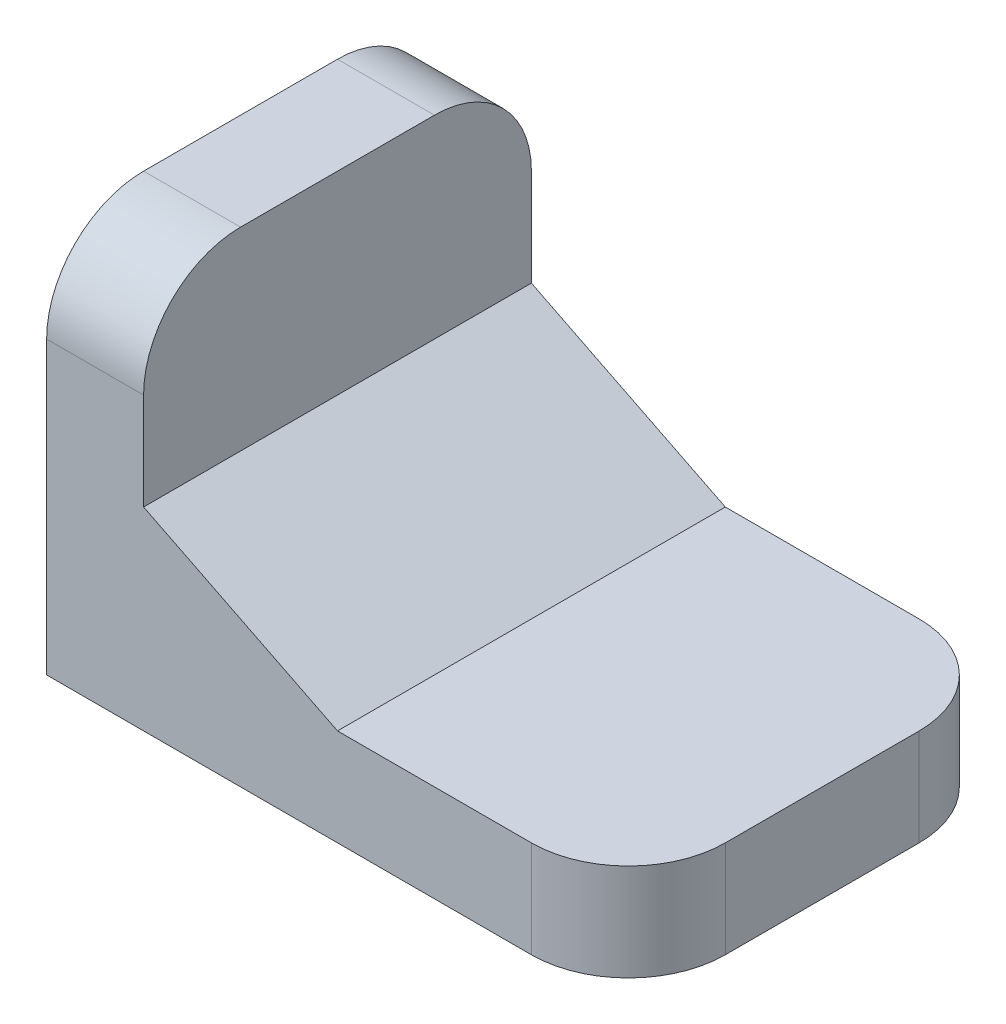
SolidWorks part; units mm, degrees
ref_plane "前基準面" through (0, 0, 0) normal (0, 0, 1) x (1, 0, 0)
ref_plane "上基準面" through (0, 0, 0) normal (0, 1, 0) x (1, 0, 0)
ref_plane "右基準面" through (0, 0, 0) normal (1, 0, 0) x (0, 0, -1)
sketch "草圖1" plane through (0, 0, 0) normal (0, 0, 1) x (1, 0, 0)
  line L0 (5, 10) -> (15, 5)
  line L2 (0, 0) -> (0, 20)
  line L3 (0, 20) -> (5, 20)
  line L4 (5, 10) -> (5, 20)
  line L5 (0, 0) -> (30, 0)
  line L7 (15, 5) -> (30, 5)
  line L8 (30, 0) -> (30, 5)
  point P6 (0.4695, 0)
  dimension "D1" = 5
  dimension "D2" = 10
  dimension "D3" = 30
  dimension "D4" = 20
  dimension "D5" = 15
  dimension "D6" = 5
  dimension "D7" = 5
extrude "填料-伸長1" add sketch "草圖1" along normal blind 20
fillet "圓角1" radius 5 4 edges at (2.5, 20, 20) (2.5, 20, 0) (30, 2.5, 20) (30, 2.5, 0)
